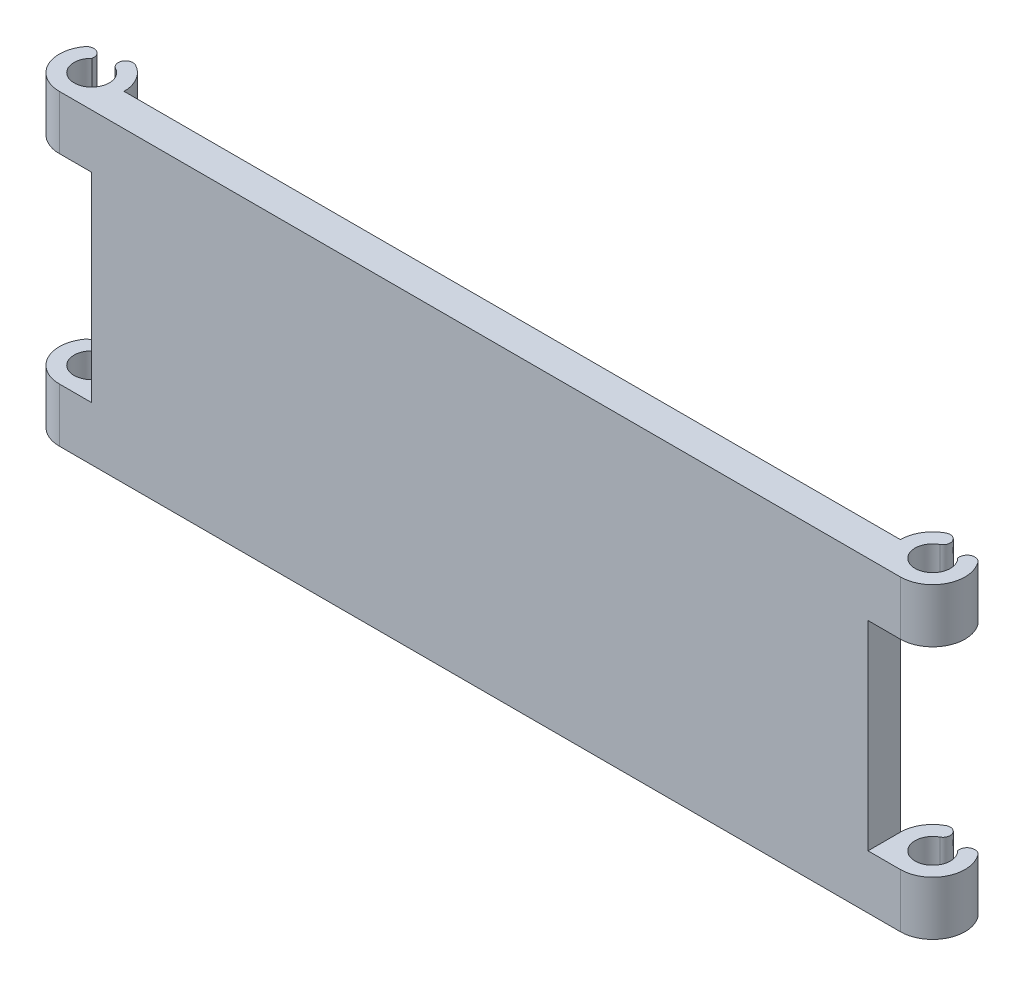
SolidWorks part; units mm, degrees
ref_plane "Plano frontal" through (0, 0, 0) normal (0, 0, 1) x (1, 0, 0)
ref_plane "Plano superior" through (0, 0, 0) normal (0, 1, 0) x (1, 0, 0)
ref_plane "Plano direito" through (0, 0, 0) normal (1, 0, 0) x (0, 0, -1)
sketch "Esboço1" plane through (0, 0, 0) normal (0, 1, 0) x (1, 0, 0)
  line L0 (-72, 0) -> (72, 0)
  line L2 (78, -6) -> (-78, -6)
  line L3 (0, 0) -> (0, -6) construction
  arc A0 (-80.2962, 2.3351) -> (-76.4496, 2.8847) centre (-78, 0) ccw
  arc A1 (-72, 0) -> (-75.1595, 5.285) centre (-78, 0) ccw
  arc A2 (-82.8639, 3.5132) -> (-78, -6) centre (-78, 0) ccw
  arc A3 (-80.2962, 2.3351) -> (-82.8639, 3.5132) centre (-81.6966, 2.6701) ccw
  arc A4 (-76.4496, 2.8847) -> (-75.1595, 5.285) centre (-75.8045, 4.0849) cw
  arc A5 (76.4496, 2.8847) -> (75.1595, 5.285) centre (75.8045, 4.0849) ccw
  arc A6 (80.2962, 2.3351) -> (82.8639, 3.5132) centre (81.6966, 2.6701) cw
  arc A7 (82.8639, 3.5132) -> (78, -6) centre (78, 0) cw
  arc A8 (72, 0) -> (75.1595, 5.285) centre (78, 0) cw
  arc A9 (80.2962, 2.3351) -> (76.4496, 2.8847) centre (78, 0) cw
  dimension "D1" = 6.55
  dimension "D2" = 12
  dimension "D4" = 3.8467
  dimension "D3" = 78
  dimension "D5" = 2.825
  dimension "D6" = 2.4003
extrude "Ressalto-extrusão1" add sketch "Esboço1" along normal blind 57
sketch3d "3DSketch2" plane through (0, 0, 0) normal (0, 0, 1) x (1, 0, 0)
  dimension "D1" = 28.5
sketch "Esboço3" plane through (0, 28.5, 0) normal (0, 1, 0) x (1, 0, 0)
  line L0 (-72, 0) -> (-72, -6)
  line L1 (-78, -6) -> (78, -6) construction
  line L2 (-78, -6) -> (-72, -6)
  line L3 (72, 0) -> (72, -6)
  line L4 (78, -6) -> (72, -6)
  arc A0 (-72, 0) -> (-78, -6) centre (-78, 0) ccw
  arc A1 (78, -6) -> (72, 0) centre (78, 0) ccw
extrude "Corte-extrusão1" cut sketch "Esboço3" against normal mid plane 37
